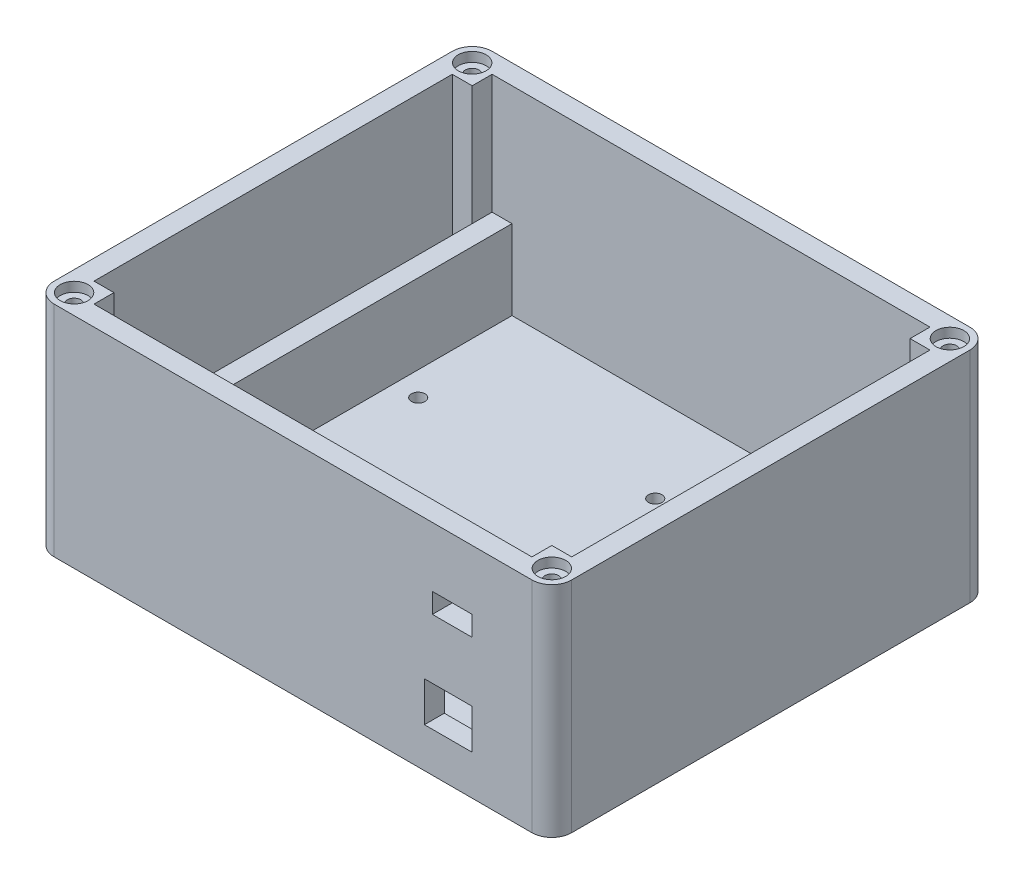
SolidWorks part; units mm, degrees
ref_plane "Front Plane" through (0, 0, 0) normal (0, 0, 1) x (1, 0, 0)
ref_plane "Top Plane" through (0, 0, 0) normal (0, 1, 0) x (1, 0, 0)
ref_plane "Right Plane" through (0, 0, 0) normal (1, 0, 0) x (0, 0, -1)
sketch "Sketch1" plane through (0, 0, 0) normal (0, 1, 0) x (1, 0, 0)
  line L1 (0, 0) -> (130, 0)
  line L2 (0, 0) -> (0, -110)
  line L3 (0, -110) -> (130, -110)
  line L4 (130, 0) -> (130, -110)
  dimension "D1" = 110
  dimension "D2" = 130
extrude "Boss-Extrude1" add sketch "Sketch1" along normal blind 5
sketch "Sketch2" plane through (0, 5, 0) normal (0, 1, 0) x (1, 0, 0)
  line L1 (0, -110) -> (130, -110)
  line L2 (0, -110) -> (0, 0)
  line L3 (0, 0) -> (130, 0)
  line L4 (130, -110) -> (130, 0)
  line L5 (10, -105) -> (120, -105)
  line L6 (5, -100) -> (5, -10)
  line L7 (10, -5) -> (120, -5)
  line L8 (125, -100) -> (125, -10)
  line L11 (5, -100) -> (10, -100)
  line L12 (10, -105) -> (10, -100)
  line L16 (5, -10) -> (10, -10)
  line L17 (10, -5) -> (10, -10)
  line L19 (125, -10) -> (120, -10)
  line L20 (120, -5) -> (120, -10)
  line L23 (125, -100) -> (120, -100)
  line L24 (120, -105) -> (120, -100)
  dimension "D1" = 5
  dimension "D2" = 5
  dimension "D3" = 5
  dimension "D4" = 5
  dimension "D5" = 5
  dimension "D6" = 5
  dimension "D7" = 5
  dimension "D8" = 5
  dimension "D9" = 5
  dimension "D10" = 5
  dimension "D11" = 5
  dimension "D12" = 5
extrude "Boss-Extrude2" add sketch "Sketch2" along normal blind 50
hole_wizard "CBORE for M3 Pan Head Machine Screw1" positions "Sketch5" profile "Sketch3" counterbore size "M3" standard "ANSI Metric"
sketch "Sketch5" plane through (0, 55, 0) normal (0, 1, 0) x (1, 0, 0)
  line L0 (130, 0) -> (0, 0) construction
  line L1 (130, -110) -> (130, 0) construction
  line L2 (0, 0) -> (0, -110) construction
  line L3 (0, -110) -> (130, -110) construction
  point P0 (5, -5)
  point P2 (125, -105)
  point P4 (5, -105)
  point P6 (125, -5)
  dimension "D1" = 5
  dimension "D2" = 5
  dimension "D3" = 5
  dimension "D4" = 5
  dimension "D5" = 5
  dimension "D6" = 5
  dimension "D7" = 5
  dimension "D8" = 5
sketch "Sketch3" plane through (5, 55, 5) normal (1, 0, 0) x (0, 0, 1)
  line L0 (0, 0) -> (0, 8.0215)
  line L1 (0, 8.0215) -> (1.7, 7)
  line L2 (1.7, 7) -> (1.7, 2.4)
  line L3 (1.7, 2.4) -> (3.5, 2.4)
  line L4 (3.5, 2.4) -> (3.5, 0)
  line L5 (3.5, 0) -> (0, 0)
  line L10 (0, 8.0215) -> (-1.7, 7) construction
  line L11 (0, -6.35) -> (0, 107.95) construction
  dimension "Hole Dia." = 3.4
  dimension "Hole Depth" = 7
  dimension "C'Bore Dia." = 7
  dimension "C'Bore Depth" = 2.4
  dimension "Drill Angle" = 118
hole_wizard "CBORE for M3 Pan Head Machine Screw2" positions "Sketch7" profile "Sketch6" counterbore size "M3" standard "ANSI Metric"
sketch "Sketch7" plane through (0, 0, 0) normal (0, -1, 0) x (-1, 0, 0)
  line L3 (-74.07, -75.08) -> (-72.8, -26.82) construction
  line L4 (-72.8, -26.82) -> (-73.435, -50.95) construction
  line L5 (-73.435, -50.95) -> (-17.5552, -52.4205) construction
  point P4 (-74.07, -75.08)
  point P6 (-72.8, -26.82)
  point P20 (-22.5388, -62.5329)
  point P21 (-21.0693, -34.6316)
  dimension "D2" = 48.26
sketch "Sketch6" plane through (74.07, 0, 75.08) normal (1, 0, 0) x (0, 0, -1)
  line L0 (0, 0) -> (0, 8.0215)
  line L1 (0, 8.0215) -> (1.7, 7)
  line L2 (1.7, 7) -> (1.7, 2.4)
  line L3 (1.7, 2.4) -> (3.5, 2.4)
  line L4 (3.5, 2.4) -> (3.5, 0)
  line L5 (3.5, 0) -> (0, 0)
  line L10 (0, 8.0215) -> (-1.7, 7) construction
  line L11 (0, -6.35) -> (0, 107.95) construction
  dimension "Hole Dia." = 3.4
  dimension "Hole Depth" = 7
  dimension "C'Bore Dia." = 7
  dimension "C'Bore Depth" = 2.4
  dimension "Drill Angle" = 118
sketch "Sketch8" plane through (0, 0, 5) normal (0, 0, 1) x (1, 0, 0)
  line L0 (120, 5) -> (120, 25)
  line L1 (120, 55) -> (120, 5) construction
  line L2 (120, 5) -> (115, 5)
  line L3 (115, 25) -> (120, 25)
  line L4 (120, 5) -> (10, 5) construction
  line L5 (115, 25) -> (115, 5)
  dimension "D1" = 5
  dimension "D2" = 20
extrude "Boss-Extrude3" add sketch "Sketch8" along normal up to surface (100 mm away) up to face at (65, 30, 105)
sketch "Sketch9" plane through (0, 0, 5) normal (0, 0, 1) x (1, 0, 0)
  line L0 (10, 5) -> (10, 25)
  line L1 (10, 55) -> (10, 5) construction
  line L2 (15, 25) -> (10, 25)
  line L3 (15, 25) -> (15, 5)
  line L4 (115, 5) -> (10, 5) construction
  line L5 (15, 5) -> (10, 5)
  dimension "D1" = 5
  dimension "D2" = 20
extrude "Boss-Extrude4" add sketch "Sketch9" along normal up to surface (100 mm away) up to face at (81.6667, 28.3333, 105)
sketch "Sketch10" plane through (0, 0, 110) normal (0, 0, 1) x (1, 0, 0)
  line L0 (130, 55) -> (130, 0) construction
  line L1 (110, 10) -> (98, 10)
  line L2 (110, 10) -> (110, 20)
  line L3 (110, 20) -> (98, 20)
  line L4 (98, 10) -> (98, 20)
  line L5 (0, 0) -> (130, 0) construction
  dimension "D1" = 10
  dimension "D2" = 12
  dimension "D3" = 20
  dimension "D4" = 10
extrude "Cut-Extrude2" cut sketch "Sketch10" against normal up to next
sketch "Sketch11" plane through (0, 0, 110) normal (0, 0, 1) x (1, 0, 0)
  line L0 (130, 55) -> (130, 0) construction
  line L1 (110, 35) -> (100, 35)
  line L2 (110, 35) -> (110, 40)
  line L3 (110, 40) -> (100, 40)
  line L4 (100, 35) -> (100, 40)
  line L5 (0, 55) -> (130, 55) construction
  dimension "D1" = 5
  dimension "D2" = 10
  dimension "D3" = 20
  dimension "D4" = 20
extrude "Cut-Extrude3" cut sketch "Sketch11" against normal up to next
fillet "Fillet6" radius 5 4 edges at (130, 27.5, 110) (130, 27.5, 0) (0, 27.5, 110) (0, 27.5, 0)
